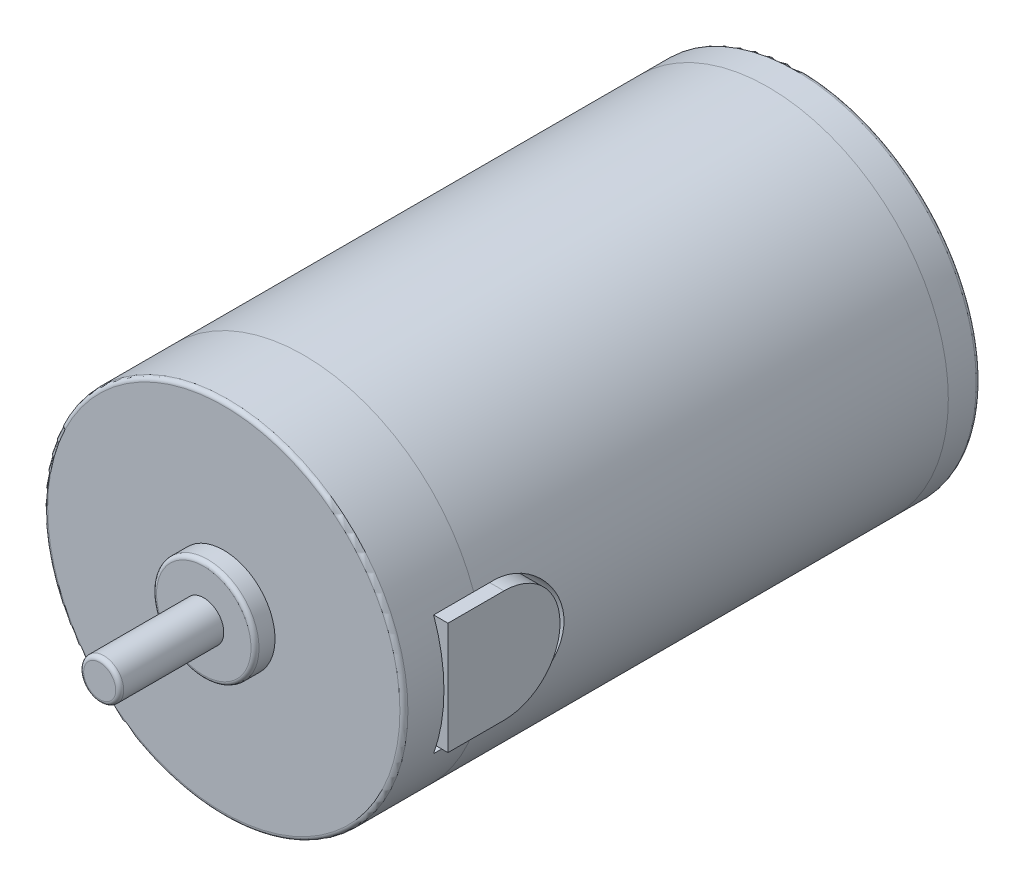
SolidWorks part; units mm, degrees
ref_plane "Front Plane" through (0, 0, 0) normal (0, 0, 1) x (1, 0, 0)
ref_plane "Top Plane" through (0, 0, 0) normal (0, 1, 0) x (1, 0, 0)
ref_plane "Right Plane" through (0, 0, 0) normal (1, 0, 0) x (0, 0, -1)
sketch "Sketch1" plane through (0, 0, 0) normal (1, 0, 0) x (0, 0, -1)
  line L0 (0, 0) -> (-87.5, 0) construction
  line L1 (0, 0) -> (0, 22.5)
  line L2 (0, 22.5) -> (-72, 22.5)
  line L3 (-72, 22.5) -> (-72, 6.4)
  line L4 (-72, 6.4) -> (-74.5, 6.4)
  line L5 (-74.5, 6.4) -> (-74.5, 2.5)
  line L8 (-87.5, 0) -> (0, 0)
  line L9 (-74.5, 2.5) -> (-87.5, 2.5)
  line L10 (-87.5, 2.5) -> (-87.5, 0)
  dimension "D1" = 22.5
  dimension "D2" = 72
  dimension "D3" = 13
  dimension "D4" = 6.4
  dimension "D5" = 2.5
  dimension "D6" = 2.5
revolve "Revolve1" add sketch "Sketch1" angle 360 about L0
sketch "Sketch2" plane through (0, 0, 0) normal (1, 0, 0) x (0, 0, -1)
  line L0 (-62, 22.5) -> (-62, -22.5)
  line L1 (-4, 22.5) -> (-4, -22.5)
  line L2 (-72, 22.5) -> (-72, -22.5) construction
  line L3 (0, -22.5) -> (0, 22.5) construction
  line L4 (0, 22.5) -> (-72, 22.5) construction
  dimension "D1" = 10
  dimension "D2" = 4
  dimension "D3" = 45
split line "Split Line1"
fillet "Fillet1" radius 0.5 4 edges at (-6.4, 0, 74.5) (-22.5, 0, 0) (-22.5, 0, 72) (-2.5, 0, 87.5)
ref_plane "Plane1" through (22.5, 0, 0) normal (1, 0, 0) x (0, 0, -1)
sketch "Sketch3" plane through (22.5, 0, 0) normal (1, 0, 0) x (0, 0, -1)
  line L0 (0, 0) -> (-87.5, 0) construction
  line L1 (-87.5, 2) -> (-87.5, -2) construction
  line L2 (-67, -7.5) -> (-67, 7.5)
  line L3 (-67, 7.5) -> (-59.5, 7.5)
  line L4 (-72, 22) -> (-72, -22) construction
  line L5 (-67, -7.5) -> (-59.5, -7.5)
  arc A0 (-59.5, -7.5) -> (-59.5, 7.5) centre (-59.5, 0) ccw
  point P10 (-52, 0)
  point P14 (-67, 0)
  dimension "D1" = 7.5
  dimension "D2" = 5
  dimension "D3" = 15
extrude "Cut-Extrude1" cut sketch "Sketch3" against normal blind 5
sketch "Sketch4" plane through (17.5, 0, 0) normal (1, 0, 0) x (0, 0, -1)
  line L0 (-67, -7.5) -> (-59.5, -7.5) construction
  line L1 (-67, 7.5) -> (-67, -7.5) construction
  line L2 (-59.5, 7.5) -> (-67, 7.5) construction
  line L3 (-67, -7.5) -> (-59.5, -7.5) construction
  line L4 (-67, 7.5) -> (-67, -7.5) construction
  line L5 (-59.5, 7.5) -> (-67, 7.5) construction
  line L6 (-66.5, -7) -> (-59.5, -7)
  line L7 (-59.5, 7) -> (-66.5, 7)
  line L8 (-66.5, 7) -> (-66.5, -7)
  arc A0 (-59.5, -7.5) -> (-59.5, 7.5) centre (-59.5, 0) ccw construction
  arc A1 (-59.5, -7.5) -> (-59.5, 7.5) centre (-59.5, 0) ccw construction
  arc A2 (-59.5, -7) -> (-59.5, 7) centre (-59.5, 0) ccw
  dimension "D1" = 0.5
extrude "Boss-Extrude1" add sketch "Sketch4" along normal blind 5
mirror "Mirror1" about plane through (0, 0, 0) normal (1, 0, 0) of "Boss-Extrude1", "Cut-Extrude1"
